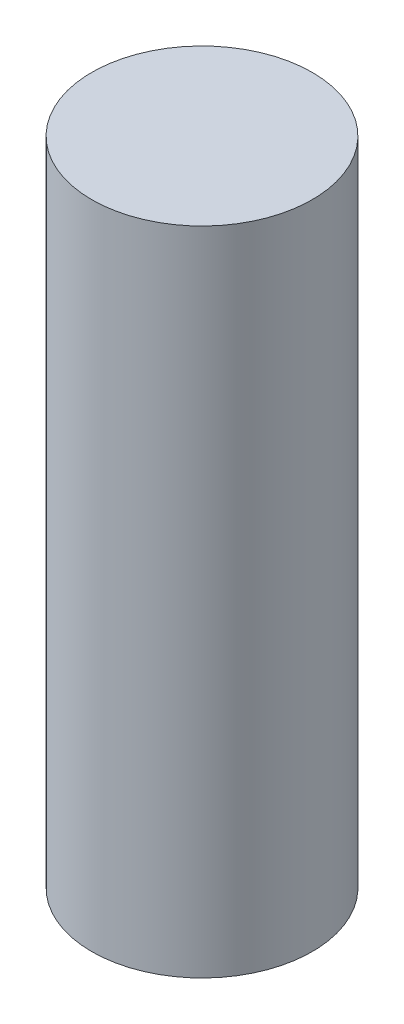
SolidWorks part; units mm, degrees
ref_plane "Front Plane" through (0, 0, 0) normal (0, 0, 1) x (1, 0, 0)
ref_plane "Top Plane" through (0, 0, 0) normal (0, 1, 0) x (1, 0, 0)
ref_plane "Right Plane" through (0, 0, 0) normal (1, 0, 0) x (0, 0, -1)
sketch "Sketch1" plane through (0, 0, 0) normal (0, 1, 0) x (1, 0, 0)
  line L0 (23.8, -72.3878) -> (23.8, 72.3878)
  line L1 (-76.2, 0) -> (76.2, 0) construction
  circle A0 centre (0, 0) radius 76.2
  dimension "D1" = 152.4
  dimension "D2" = 100
extrude "Boss-Extrude1" add sketch "Sketch1" along normal blind 450 contours L1 L0 A0 | L0 L1 A0
sketch "Sketch2" plane through (0, 0, 0) normal (0, 1, 0) x (1, 0, 0)
  line L0 (23.8, 72.3878) -> (23.8, -72.3878)
  line L1 (76.2, 0) -> (-76.2, 0) construction
  circle A0 centre (0, 0) radius 76.2
  dimension "D1" = 152.4
  dimension "D2" = 100
extrude "Boss-Extrude2" add sketch "Sketch2" along normal blind 450 contours L0 L1 A0 | L1 L0 A0
